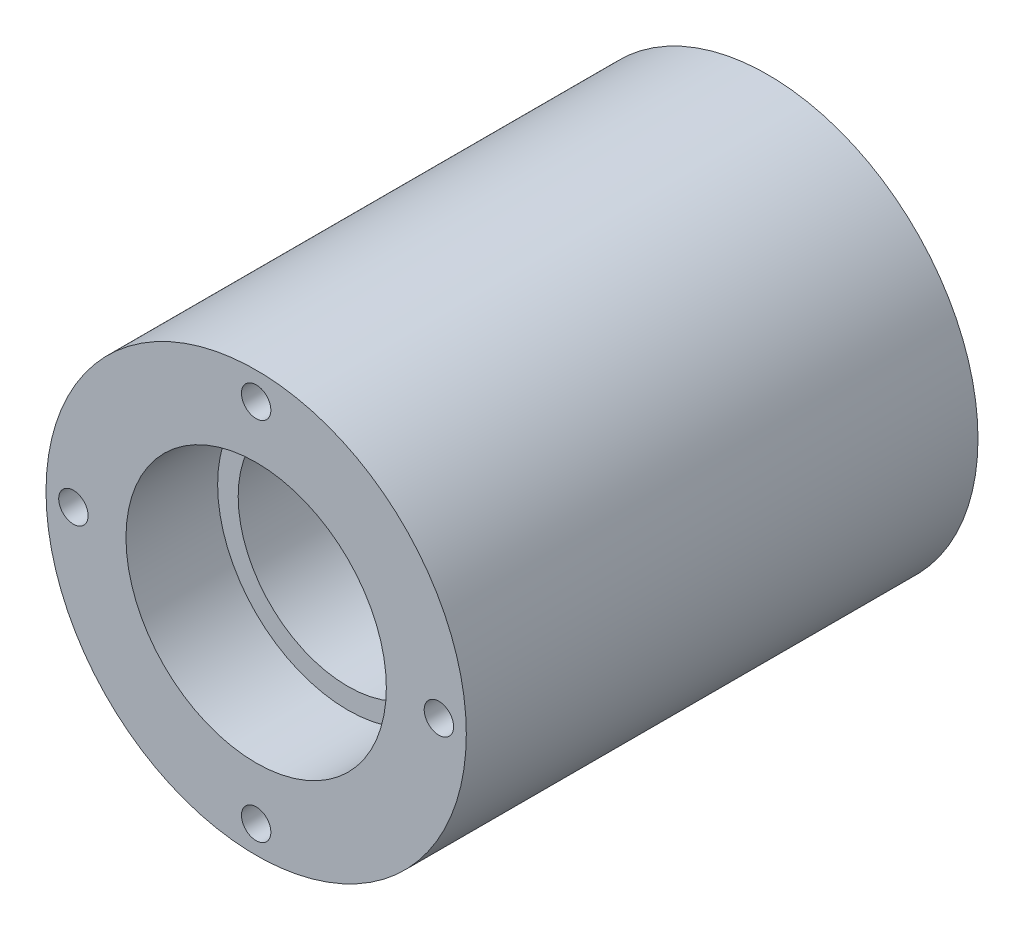
SolidWorks part; units mm, degrees
ref_plane "Front Plane" through (0, 0, 0) normal (0, 0, 1) x (1, 0, 0)
ref_plane "Top Plane" through (0, 0, 0) normal (0, 1, 0) x (1, 0, 0)
ref_plane "Right Plane" through (0, 0, 0) normal (1, 0, 0) x (0, 0, -1)
sketch "Sketch1" plane through (0, 0, 0) normal (0, 0, 1) x (1, 0, 0)
  circle A0 centre (0, 0) radius 36.5125
  circle A1 centre (0, 0) radius 19.05
  dimension "D1" = 73.025
  dimension "D2" = 38.1
extrude "Extrude1" add sketch "Sketch1" along normal mid plane 88.9
sketch "Sketch3" plane through (0, 0, 44.45) normal (0, 0, 1) x (1, 0, 0)
  circle A0 centre (0, 0) radius 22.6187
  circle A1 centre (0, 0) radius 19.05 construction
  dimension "D1" = 45.2374
extrude "Outer race pocket master" cut sketch "Sketch3" against normal blind 15.9258
hole_wizard "1/4-20 thread pattern master" positions "Sketch9" profile "Sketch8" tap size "1/4-20" standard "Ansi Inch"
sketch "Sketch9" plane through (0, 0, 44.45) normal (0, 0, 1) x (1, 0, 0)
  circle A0 centre (0, 0) radius 31.75 construction
  point P0 (0, 31.75)
  point P2 (31.75, 0)
  point P4 (0, -31.75)
  point P6 (-31.75, 0)
  dimension "D1" = 63.5
sketch "Sketch8" plane through (0, 31.75, 44.45) normal (1, 0, 0) x (0, -1, 0)
  line L0 (0, 0) -> (0, 11.0588)
  line L1 (0, 11.0588) -> (2.5527, 9.525)
  line L2 (2.5527, 9.525) -> (2.5527, 0)
  line L5 (2.5527, 0) -> (0, 0)
  line L10 (0, 11.0588) -> (-2.5527, 9.525) construction
  line L11 (0, -6.35) -> (0, 107.95) construction
  dimension "Tap Drill Dia." = 5.1054
  dimension "Tap Drill Depth" = 9.525
  dimension "Drill Angle" = 118
cosmetic thread "Hole Thread6" parameters "D1"=9.525, "D2"=6.35
cosmetic thread "Hole Thread7" parameters "D1"=9.525, "D2"=6.35
cosmetic thread "Hole Thread8" parameters "D1"=9.525, "D2"=6.35
cosmetic thread "Hole Thread9" parameters "D1"=9.525, "D2"=6.35
mirror "Pocket and thread mirror" about plane through (0, 0, 0) normal (0, 0, 1) of "Outer race pocket master", "1/4-20 thread pattern master"
fillet "Fillet1" [suppressed] radius 1.27
